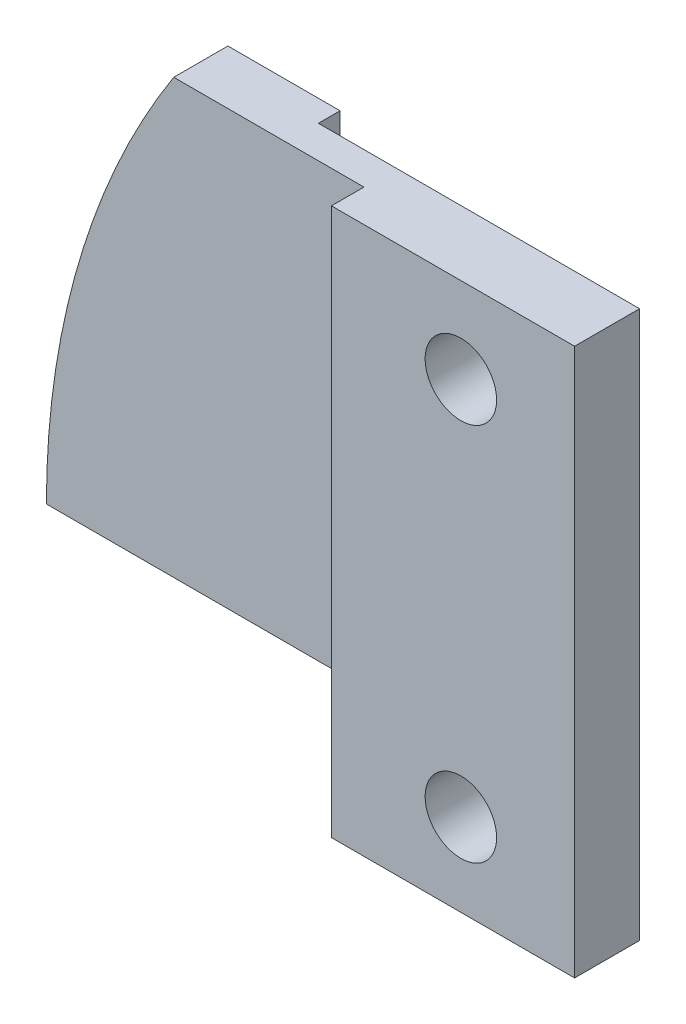
SolidWorks part; units mm, degrees
ref_plane "Front Plane" through (0, 0, 0) normal (0, 0, 1) x (1, 0, 0)
ref_plane "Top Plane" through (0, 0, 0) normal (0, 1, 0) x (1, 0, 0)
ref_plane "Right Plane" through (0, 0, 0) normal (1, 0, 0) x (0, 0, -1)
sketch "Sketch1" plane through (0, 0, 0) normal (0, 0, 1) x (1, 0, 0)
  line L11 (-8.0046, 23.2577) -> (12, 23.2577)
  line L12 (12, 23.2577) -> (12, 0)
  line L14 (0.7757, 0) -> (0.7757, -2)
  line L15 (0.7757, -2) -> (12, -2)
  line L16 (12, -2) -> (12, 0)
  line L17 (-13.8827, 3.2577) -> (0.7757, 3.2577)
  line L18 (0.7757, 3.2577) -> (0.7757, 0)
  circle A2 centre (6.7492, 19.3061) radius 1.65
  circle A3 centre (6.7492, 1.8061) radius 1.65
  arc A4 (-13.8827, 3.2577) -> (-8.0046, 23.2577) centre (23.081, 3.2577) cw
  point P16 (6.7492, 19.3061)
  dimension "D1" = 20
  dimension "D3" = 36.9636
  dimension "D2" = 3.3
  dimension "D7" = 23.081
  dimension "D8" = 1.8061
  dimension "D4" = 0.7757
  dimension "D5" = 6.7492
  dimension "D6" = 12
  dimension "D9" = 3.2577
  dimension "D10" = 19.3061
  dimension "D12" = 2
extrude "Boss-Extrude1" add sketch "Sketch1" along normal blind 2.5
sketch "Sketch5" plane through (0, 0, 2.5) normal (0, 0, 1) x (1, 0, 0)
  line L0 (0.7757, 3.2577) -> (0.7757, 23.2577)
  line L1 (12, 23.2577) -> (-8.0046, 23.2577) construction
  line L2 (0.7757, 23.2577) -> (12, 23.2577)
  line L3 (12, 23.2577) -> (12, -2)
  line L4 (12, -2) -> (0.7757, -2)
  line L5 (0.7757, -2) -> (0.7757, 3.2577)
  circle A0 centre (6.7492, 19.3061) radius 1.65
  circle A1 centre (6.7492, 1.8061) radius 1.65
extrude "Boss-Extrude2" add sketch "Sketch5" along normal blind 1.5
sketch "Sketch6" plane through (0, 0, 0) normal (0, 0, -1) x (-1, 0, 0)
  line L0 (-12, 23.2577) -> (-12, -2)
  line L1 (-12, -2) -> (-0.7757, -2)
  line L2 (-0.7757, -2) -> (-0.7757, 3.2577)
  line L3 (-0.7757, 3.2577) -> (2.8267, 3.2577)
  line L4 (13.8827, 3.2577) -> (-0.7757, 3.2577) construction
  line L5 (2.8267, 3.2577) -> (2.8267, 23.2577)
  line L6 (-12, 23.2577) -> (8.0046, 23.2577) construction
  line L7 (2.8267, 23.2577) -> (-12, 23.2577)
extrude "Cut-Extrude3" cut sketch "Sketch6" against normal blind 1
